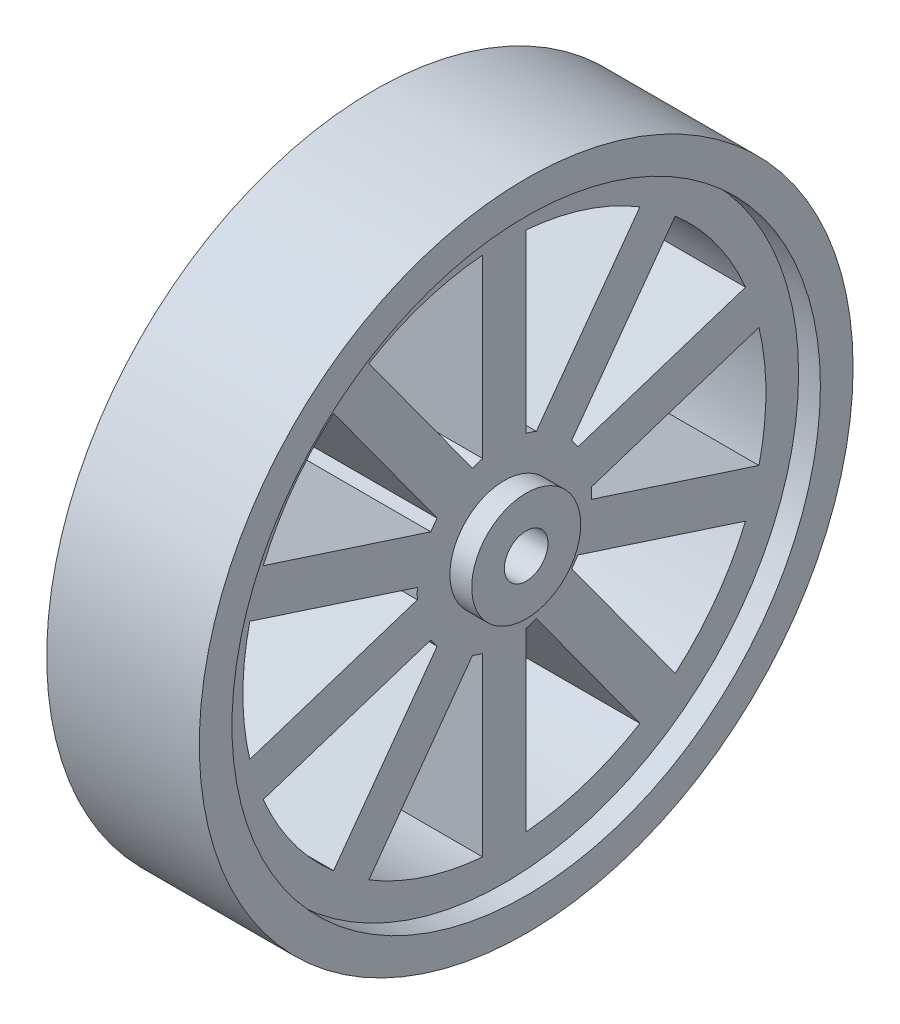
SolidWorks part; units mm, degrees
ref_plane "Front Plane" through (0, 0, 0) normal (0, 0, 1) x (1, 0, 0)
ref_plane "Top Plane" through (0, 0, 0) normal (0, 1, 0) x (1, 0, 0)
ref_plane "Right Plane" through (0, 0, 0) normal (1, 0, 0) x (0, 0, -1)
sketch "Sketch1" plane through (0, 0, 0) normal (1, 0, 0) x (0, 0, -1)
  circle A0 centre (0, 0) radius 2.54
  circle A1 centre (0, 0) radius 38.1
  dimension "D1" = 5.08
  dimension "D2" = 76.2
extrude "Boss-Extrude1" add sketch "Sketch1" along normal mid plane 17.78
sketch "Sketch2" plane through (8.89, 0, 0) normal (1, 0, 0) x (0, 0, -1)
  line L0 (0, -1010.16) -> (0, -10.16) construction
  line L1 (-2.54, 30.374) -> (-2.54, 9.8374)
  line L2 (2.54, 30.374) -> (2.54, 9.8374)
  line L3 (19.9083, 23.0801) -> (7.8372, 6.4656)
  line L4 (15.7985, 26.066) -> (3.7274, 9.4516)
  line L5 (29.6723, 6.9704) -> (10.1408, 0.6242)
  line L6 (28.1025, 11.8018) -> (8.571, 5.4556)
  line L7 (28.1025, -11.8018) -> (8.571, -5.4556)
  line L8 (29.6723, -6.9704) -> (10.1408, -0.6242)
  line L9 (15.7985, -26.066) -> (3.7274, -9.4516)
  line L10 (19.9083, -23.0801) -> (7.8372, -6.4656)
  line L11 (-2.54, -30.374) -> (-2.54, -9.8374)
  line L12 (2.54, -30.374) -> (2.54, -9.8374)
  line L13 (-19.9083, -23.0801) -> (-7.8372, -6.4656)
  line L14 (-15.7985, -26.066) -> (-3.7274, -9.4516)
  line L15 (-29.6723, -6.9704) -> (-10.1408, -0.6242)
  line L16 (-28.1025, -11.8018) -> (-8.571, -5.4556)
  line L17 (-28.1025, 11.8018) -> (-8.571, 5.4556)
  line L18 (-29.6723, 6.9704) -> (-10.1408, 0.6242)
  line L19 (-15.7985, 26.066) -> (-3.7274, 9.4516)
  line L20 (-19.9083, 23.0801) -> (-7.8372, 6.4656)
  line L21 (0, 5.08) -> (0, 20.1055) construction
  arc A0 (3.7274, 9.4516) -> (2.54, 9.8374) centre (0, 0) ccw
  circle A1 centre (0, 0) radius 2.54 construction
  arc A2 (15.7985, 26.066) -> (2.54, 30.374) centre (0, 0) ccw
  circle A3 centre (0, 0) radius 38.1 construction
  arc A4 (-2.54, 30.374) -> (-15.7985, 26.066) centre (0, 0) ccw
  arc A5 (-2.54, 9.8374) -> (-3.7274, 9.4516) centre (0, 0) ccw
  arc A6 (8.571, 5.4556) -> (7.8372, 6.4656) centre (0, 0) ccw
  arc A7 (28.1025, 11.8018) -> (19.9083, 23.0801) centre (0, 0) ccw
  arc A8 (10.1408, -0.6242) -> (10.1408, 0.6242) centre (0, 0) ccw
  arc A9 (29.6723, -6.9704) -> (29.6723, 6.9704) centre (0, 0) ccw
  arc A10 (7.8372, -6.4656) -> (8.571, -5.4556) centre (0, 0) ccw
  arc A11 (19.9083, -23.0801) -> (28.1025, -11.8018) centre (0, 0) ccw
  arc A12 (-19.9083, 23.0801) -> (-28.1025, 11.8018) centre (0, 0) ccw
  arc A13 (-7.8372, 6.4656) -> (-8.571, 5.4556) centre (0, 0) ccw
  arc A14 (-10.1408, 0.6242) -> (-10.1408, -0.6242) centre (0, 0) ccw
  arc A15 (-29.6723, 6.9704) -> (-29.6723, -6.9704) centre (0, 0) ccw
  arc A16 (-28.1025, -11.8018) -> (-19.9083, -23.0801) centre (0, 0) ccw
  arc A17 (-8.571, -5.4556) -> (-7.8372, -6.4656) centre (0, 0) ccw
  arc A18 (-3.7274, -9.4516) -> (-2.54, -9.8374) centre (0, 0) ccw
  arc A19 (-15.7985, -26.066) -> (-2.54, -30.374) centre (0, 0) ccw
  arc A20 (2.54, -9.8374) -> (3.7274, -9.4516) centre (0, 0) ccw
  arc A21 (2.54, -30.374) -> (15.7985, -26.066) centre (0, 0) ccw
  point P14 (0, 0)
  point P15 (0, 0)
  point P53 (0, 0)
  dimension "D1" = 7.62
  dimension "D2" = 7.62
  dimension "D3" = 5.08
  dimension "D4" = 10
extrude "Cut-Extrude1" cut sketch "Sketch2" against normal through all both and the other way through all
sketch "Sketch3" plane through (8.89, 0, 0) normal (1, 0, 0) x (0, 0, -1)
  circle A0 centre (0, 0) radius 6.35
  circle A1 centre (0, 0) radius 34.29
  circle A2 centre (0, 0) radius 38.1 construction
  circle A3 centre (0, 0) radius 2.54 construction
  dimension "D1" = 3.81
  dimension "D2" = 3.81
extrude "Cut-Extrude2" cut sketch "Sketch3" against normal blind 2.54
